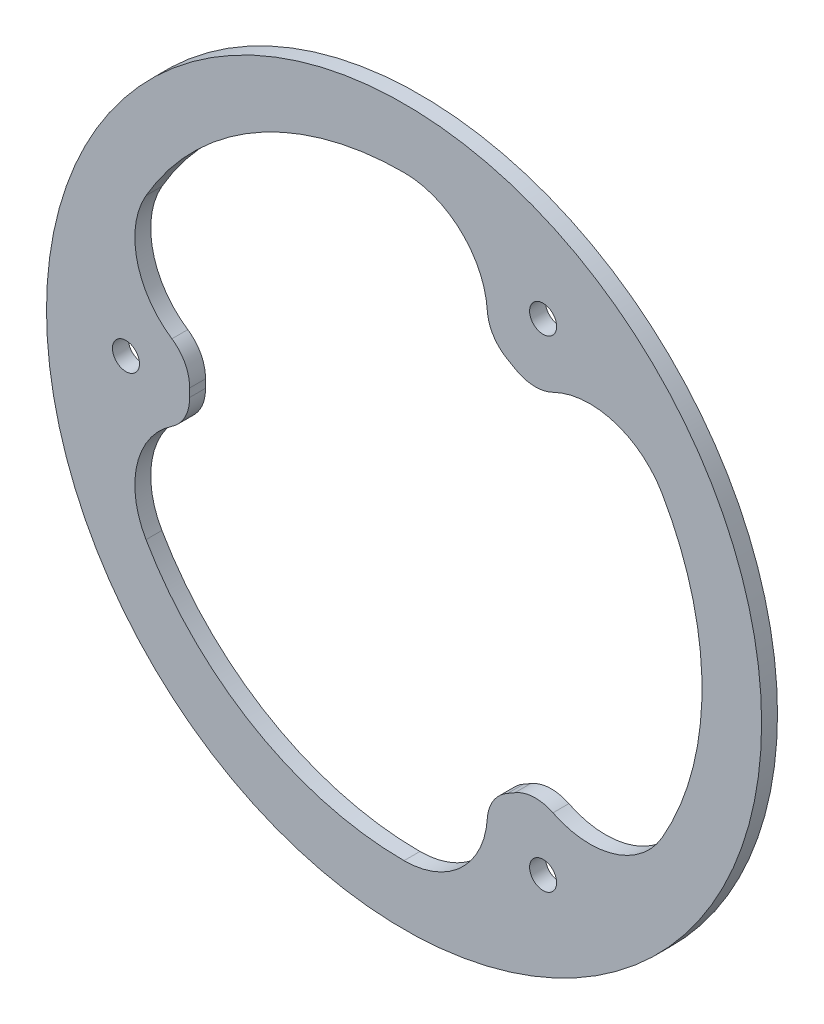
SolidWorks part; units mm, degrees
material "Сплав 2024"
ref_plane "Спереди" through (0, 0, 0) normal (0, 0, 1) x (1, 0, 0)
ref_plane "Сверху" through (0, 0, 0) normal (0, 1, 0) x (1, 0, 0)
ref_plane "Справа" through (0, 0, 0) normal (1, 0, 0) x (0, 0, -1)
sketch "Эскиз1" plane through (0, 0, 0) normal (0, 0, 1) x (1, 0, 0)
  circle A0 centre (0, 0) radius 40
  dimension "D1" = 80
extrude "Бобышка-Вытянуть1" add sketch "Эскиз1" along normal blind 12
sketch "Эскиз8" plane through (0, 0, 12) normal (0, 0, 1) x (1, 0, 0)
  circle A0 centre (0, 0) radius 45
  dimension "D1" = 90
extrude "Бобышка-Вытянуть3" add sketch "Эскиз8" along normal blind 2
sketch "Эскиз2" plane through (0, 0, 14) normal (0, 0, -1) x (-1, 0, 0)
  circle A0 centre (0, 0) radius 7.5
  dimension "D1" = 15
extrude "Вырез-Вытянуть1" cut sketch "Эскиз2" along normal through all
hole_wizard "Отверстие с зазором M31" positions "Эскиз4" profile "Эскиз3" hole size "M3" standard "Ansi Metric"
sketch "Эскиз4" plane through (-6.6635, -3.8899, 14) normal (0, 0, -1) x (-1, 0, 0)
  point P0 (20.5996, 37.0106)
sketch "Эскиз3" plane through (-27.2631, 33.1208, 14) normal (1, 0, 0) x (0, -1, 0)
  line L0 (0, 0) -> (0, 14)
  line L1 (0, 14) -> (1.7, 14)
  line L2 (1.7, 14) -> (1.7, 0)
  line L5 (1.7, 0) -> (0, 0)
  line L11 (0, -6.35) -> (0, 107.95) construction
  dimension "Диаметр сквозного отверстия" = 3.4
  dimension "Глубина сквозного отверстия" = 14
sketch "Эскиз10" plane through (0, 0, 0) normal (0, 0, -1) x (-1, 0, 0)
  line L1 (0, 49.276) -> (0, -49.5343) construction
  line L2 (46.4311, 26.807) -> (-46.4311, -26.807) construction
  arc A2 (32.476, -18.75) -> (14.2894, -8.25) centre (23.3827, -13.5) ccw
  arc A3 (32.476, 18.75) -> (0, 37.5) centre (0, 0) ccw
  circle A4 centre (0, 0) radius 27 construction
  arc A5 (0, 37.5) -> (0, 16.5) centre (0, 27) ccw
  arc A6 (14.2894, 8.25) -> (32.476, 18.75) centre (23.3827, 13.5) ccw
  arc A7 (14.2894, 8.25) -> (0, 16.5) centre (0, 0) ccw
  arc A8 (0, -16.5) -> (14.2894, -8.25) centre (0, 0) ccw
  arc A9 (0, -16.5) -> (0, -37.5) centre (0, -27) ccw
  arc A10 (0, -37.5) -> (32.476, -18.75) centre (0, 0) ccw
  arc A11 (-32.476, -18.75) -> (-14.2894, -8.25) centre (-23.3827, -13.5) ccw
  arc A12 (-14.2894, 8.25) -> (-14.2894, -8.25) centre (0, 0) ccw
  arc A13 (-14.2894, 8.25) -> (-32.476, 18.75) centre (-23.3827, 13.5) ccw
  arc A14 (-32.476, 18.75) -> (-32.476, -18.75) centre (0, 0) ccw
  point P28 (0, 0)
  dimension "D1" = 3
  dimension "D2" = 75
  dimension "D3" = 54
  dimension "D4" = 60
sketch "Эскиз11" plane through (0, 0, 14) normal (0, 0, 1) x (1, 0, 0)
  line L1 (6.25, 10.8253) -> (-6.25, -10.8253) construction
  line L2 (12.5, 0) -> (-12.5, 0) construction
  line L3 (-6.25, 10.8253) -> (6.25, -10.8253) construction
  circle A0 centre (0, 0) radius 12.5 construction
  dimension "D1" = 25
  dimension "D2" = 60
  dimension "D3" = 60
hole_wizard "Отверстие с зазором M32" positions "Эскиз13" profile "Эскиз12" hole size "M3" standard "Ansi Metric" end condition through all
sketch "Эскиз13" plane through (0, 0, 14) normal (0, 0, 1) x (1, 0, 0)
  point P0 (6.25, 10.8253)
  point P3 (-12.5, 0)
  point P9 (6.25, -10.8253)
sketch "Эскиз12" plane through (6.25, 10.8253, 14) normal (1, 0, 0) x (0, -1, 0)
  line L0 (0, 0) -> (0, 14)
  line L1 (0, 14) -> (1.7, 14)
  line L2 (1.7, 14) -> (1.7, 0)
  line L5 (1.7, 0) -> (0, 0)
  line L11 (0, -6.35) -> (0, 107.95) construction
  dimension "Диаметр сквозного отверстия" = 3.4
  dimension "Глубина сквозного отверстия" = 14
extrude "Вырез-Вытянуть2" cut sketch "Эскиз10" against normal through all
sketch "Эскиз14" plane through (0, 0, 0) normal (0, 0, -1) x (-1, 0, 0)
  line L2 (-55.8661, 0) -> (55.9948, 0) construction
  line L3 (-20, 34.641) -> (20, -34.641) construction
  line L4 (20, 34.641) -> (-20, -34.641) construction
  circle A0 centre (0, 0) radius 40 construction
  circle A1 centre (0, 0) radius 40 construction
  circle A2 centre (0, 0) radius 35 construction
  dimension "D3" = 70
  dimension "D1" = 60
  dimension "D2" = 60
hole_wizard "Отверстие с зазором M33" positions "Эскиз16" profile "Эскиз15" hole size "M3" standard "Ansi Metric" end condition through all
sketch "Эскиз16" plane through (0, 0, 0) normal (0, 0, -1) x (-1, 0, 0)
  line L0 (-20, 34.641) -> (20, -34.641) construction
  line L1 (20, 34.641) -> (-20, -34.641) construction
  line L2 (-55.8661, 0) -> (55.9948, 0) construction
  circle A0 centre (0, 0) radius 35 construction
  point P0 (-17.5, 30.3109)
  point P6 (35, 0)
  point P12 (-17.5, -30.3109)
sketch "Эскиз15" plane through (17.5, 30.3109, 0) normal (1, 0, 0) x (0, 1, 0)
  line L0 (0, 0) -> (0, 14)
  line L1 (0, 14) -> (1.7, 14)
  line L2 (1.7, 14) -> (1.7, 0)
  line L5 (1.7, 0) -> (0, 0)
  line L11 (0, -6.35) -> (0, 107.95) construction
  dimension "Диаметр сквозного отверстия" = 3.4
  dimension "Глубина сквозного отверстия" = 14
sketch "Эскиз17" plane through (0, 0, 0) normal (0, 0, -1) x (-1, 0, 0)
  circle A0 centre (0, 0) radius 42.2429
extrude "Вырез-Вытянуть3" cut sketch "Эскиз17" against normal up to surface (12 mm away) up to face at (45, 0, 12)
sketch "Эскиз18" plane through (0, 0, 12) normal (0, 0, -1) x (-1, 0, 0)
  circle A0 centre (0, 0) radius 27
  dimension "D1" = 54
extrude "Вырез-Вытянуть4" cut sketch "Эскиз18" against normal through all
fillet "Скругление1" radius 5 6 edges at (-26.7643, 3.5595, 13) (-26.7643, -3.5595, 13) (16.4648, -21.3989, 13) (10.2996, -24.9583, 13) (10.2996, 24.9583, 13) (16.4648, 21.3989, 13)
